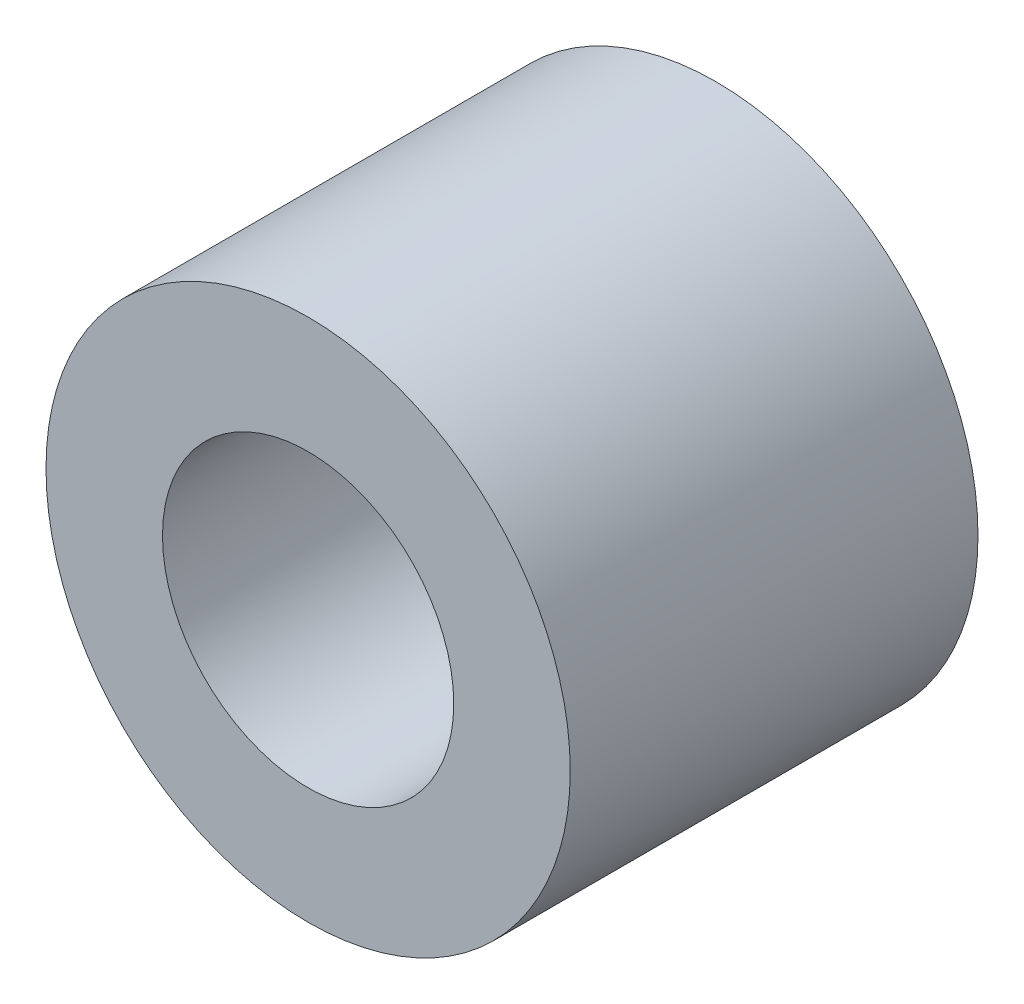
SolidWorks part; units mm, degrees
ref_plane "Plano frontal" through (0, 0, 0) normal (0, 0, 1) x (1, 0, 0)
ref_plane "Plano superior" through (0, 0, 0) normal (0, 1, 0) x (1, 0, 0)
ref_plane "Plano direito" through (0, 0, 0) normal (1, 0, 0) x (0, 0, -1)
sketch "Esboço1" plane through (0, 0, 0) normal (0, 0, 1) x (1, 0, 0)
  circle A0 centre (0, 0) radius 2.5
  circle A2 centre (0, 0) radius 4.5
  dimension "D1" = 5
  dimension "D2" = 2
extrude "Ressalto-extrusão1" add sketch "Esboço1" along normal blind 7
